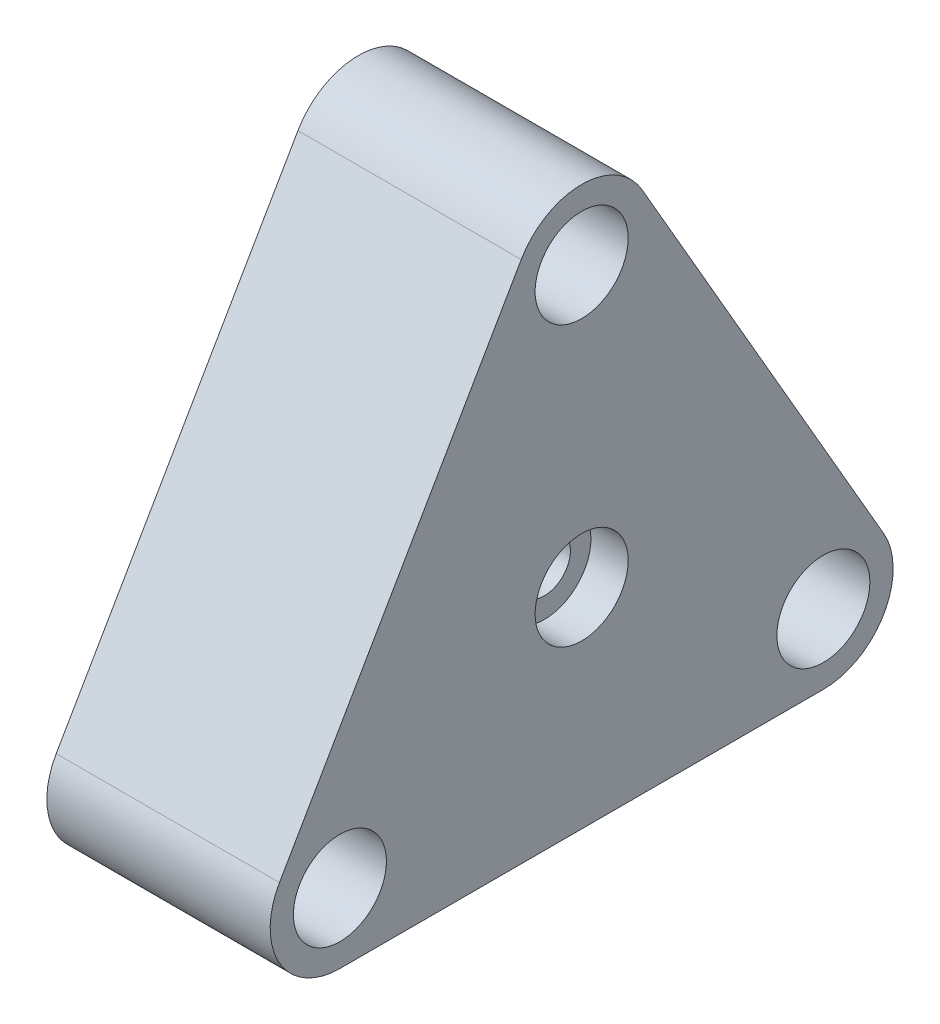
SolidWorks part; units mm, degrees
material "PE High Density"
ref_plane "Front Plane" through (0, 0, 0) normal (0, 0, 1) x (1, 0, 0)
ref_plane "Top Plane" through (0, 0, 0) normal (0, 1, 0) x (1, 0, 0)
ref_plane "Right Plane" through (0, 0, 0) normal (1, 0, 0) x (0, 0, -1)
sketch "Sketch2" plane through (0, 0, 0) normal (1, 0, 0) x (0, 0, -1)
  line L0 (0, 15) -> (0, 0) construction
  line L1 (0, 0) -> (-12.9904, -7.5) construction
  circle A0 centre (0, 0) radius 15 construction
  point P3 (0, 15)
  point P4 (-12.9904, -7.5)
  point P5 (12.9904, -7.5)
  dimension "D1" = 15
  dimension "D2" = 120
sketch "Sketch3" plane through (0, 0, 0) normal (1, 0, 0) x (0, 0, -1)
  line L0 (-16.238, -5.625) -> (-3.2476, 16.875)
  line L1 (3.2476, 16.875) -> (16.238, -5.625)
  line L2 (-12.9904, -11.25) -> (12.9904, -11.25)
  arc A0 (3.2476, 16.875) -> (-3.2476, 16.875) centre (0, 15) ccw
  arc A1 (-16.238, -5.625) -> (-12.9904, -11.25) centre (-12.9904, -7.5) ccw
  arc A2 (12.9904, -11.25) -> (16.238, -5.625) centre (12.9904, -7.5) ccw
  dimension "D1" = 3.75
extrude "Boss-Extrude1" add sketch "Sketch3" along normal mid plane 12
sketch "Sketch4" plane through (6, 0, 0) normal (1, 0, 0) x (0, 0, -1)
  circle A0 centre (0, 15) radius 2.5
  circle A1 centre (-12.9904, -7.5) radius 2.5
  circle A2 centre (12.9904, -7.5) radius 2.5
  dimension "D1" = 5
sketch "Sketch5" plane through (-6, 0, 0) normal (-1, 0, 0) x (0, 0, 1)
  circle A0 centre (0, 0) radius 2.5
  dimension "D1" = 5
extrude "Cut-Extrude1" cut sketch "Sketch4" against normal blind 6
extrude "Cut-Extrude2" cut sketch "Sketch5" against normal blind 6
hole_wizard "#3 Clearance Hole1" positions "Sketch6" profile "Sketch7" hole size "#3" standard "ANSI Inch"
sketch "Sketch6" plane through (0, 0, 0) normal (1, 0, 0) x (0, 0, -1)
  point P0 (12.9904, -7.5)
  point P3 (0, 15)
  point P6 (-12.9904, -7.5)
sketch "Sketch7" plane through (0, -7.5, -12.9904) normal (0, 1, 0) x (0, 0, -1)
  line L0 (0, 0) -> (0, 6.8394)
  line L1 (0, 6.8394) -> (1.397, 6)
  line L2 (1.397, 6) -> (1.397, 0)
  line L5 (1.397, 0) -> (0, 0)
  line L10 (0, 6.8394) -> (-1.397, 6) construction
  line L11 (0, -6.35) -> (0, 107.95) construction
  dimension "Hole Dia." = 2.794
  dimension "Hole Depth" = 6
  dimension "Drill Angle" = 118
hole_wizard "#3 Clearance Hole2" positions "Sketch8" profile "Sketch9" hole size "#3" standard "ANSI Inch"
sketch "Sketch8" plane through (0, 0, 0) normal (-1, 0, 0) x (0, 0, 1)
  point P0 (0, 0)
sketch "Sketch9" plane through (0, 0, 0) normal (0, 1, 0) x (0, 0, 1)
  line L0 (0, 0) -> (0, 6.8394)
  line L1 (0, 6.8394) -> (1.397, 6)
  line L2 (1.397, 6) -> (1.397, 0)
  line L5 (1.397, 0) -> (0, 0)
  line L10 (0, 6.8394) -> (-1.397, 6) construction
  line L11 (0, -6.35) -> (0, 107.95) construction
  dimension "Hole Dia." = 2.794
  dimension "Hole Depth" = 6
  dimension "Drill Angle" = 118
sketch "Sketch11" plane through (-6, 0, 0) normal (-1, 0, 0) x (0, 0, 1)
  circle A0 centre (0, 15) radius 2.5
  circle A1 centre (-12.9904, -7.5) radius 2.5
  circle A2 centre (12.9904, -7.5) radius 2.5
  dimension "D1" = 5
extrude "Cut-Extrude3" cut sketch "Sketch11" against normal blind 2
sketch "Sketch12" plane through (6, 0, 0) normal (1, 0, 0) x (0, 0, -1)
  circle A0 centre (0, 0) radius 2.5
  dimension "D1" = 5
extrude "Cut-Extrude4" cut sketch "Sketch12" against normal blind 2
